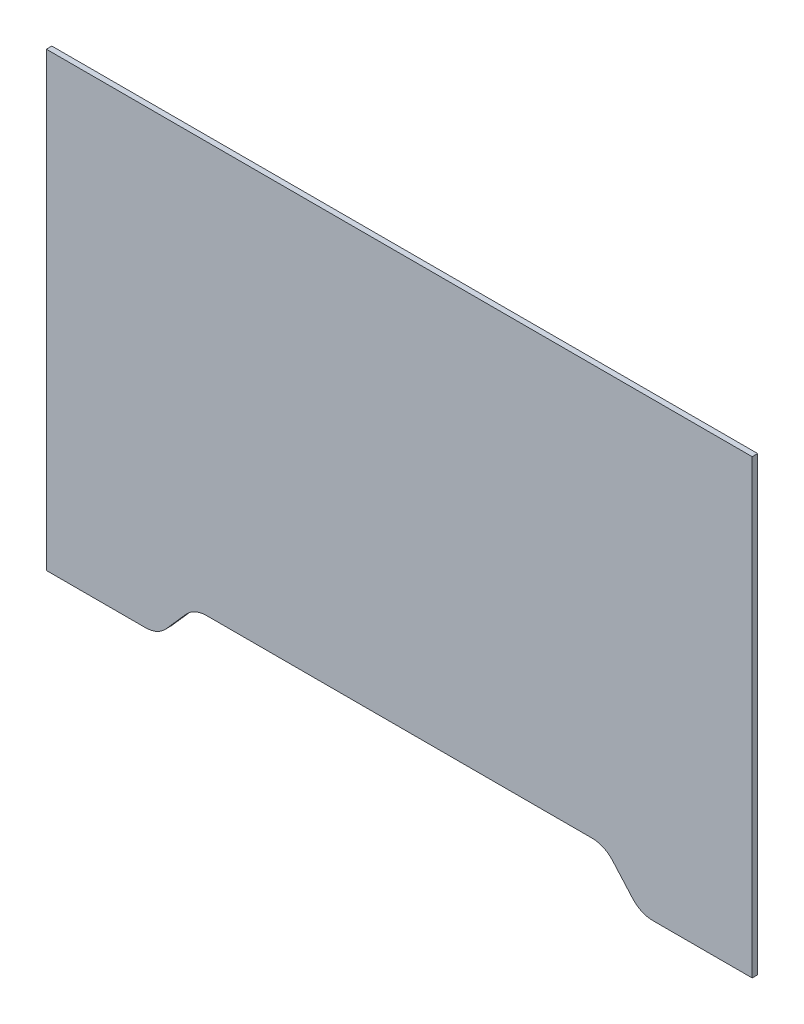
SolidWorks part; units mm, degrees
ref_plane "Front Plane" through (0, 0, 0) normal (0, 0, 1) x (1, 0, 0)
ref_plane "Top Plane" through (0, 0, 0) normal (0, 1, 0) x (1, 0, 0)
ref_plane "Right Plane" through (0, 0, 0) normal (1, 0, 0) x (0, 0, -1)
sketch "Sketch1" plane through (0, 0, 0) normal (0, 0, 1) x (1, 0, 0)
  line L0 (-170.4858, -158.2288) -> (-155.9717, -141.7712)
  line L1 (-258, -165) -> (-185.4858, -165)
  line L2 (-258, -165) -> (-258, 165)
  line L3 (-258, 165) -> (258, 165)
  line L4 (258, -165) -> (258, 165)
  line L5 (-258, -165) -> (258, 165) construction
  line L6 (-258, 165) -> (258, -165) construction
  line L7 (-140.9717, -135) -> (140.9717, -135)
  line L8 (155.9717, -141.7712) -> (170.4858, -158.2288)
  line L9 (185.4858, -165) -> (258, -165)
  arc A0 (170.4858, -158.2288) -> (185.4858, -165) centre (185.4858, -145) ccw
  arc A1 (140.9717, -135) -> (155.9717, -141.7712) centre (140.9717, -155) cw
  arc A2 (-155.9717, -141.7712) -> (-140.9717, -135) centre (-140.9717, -155) cw
  arc A3 (-170.4858, -158.2288) -> (-185.4858, -165) centre (-185.4858, -145) cw
  point P0 (0, 0)
  point P12 (176.4575, -165)
  point P15 (150, -135)
  point P18 (-150, -135)
  point P21 (-176.4575, -165)
  dimension "D6" = 20
  dimension "D1" = 516
  dimension "D2" = 330
  dimension "D3" = 300
  dimension "D4" = 40
  dimension "D5" = 30
extrude "Boss-Extrude1" add sketch "Sketch1" along normal blind 4
